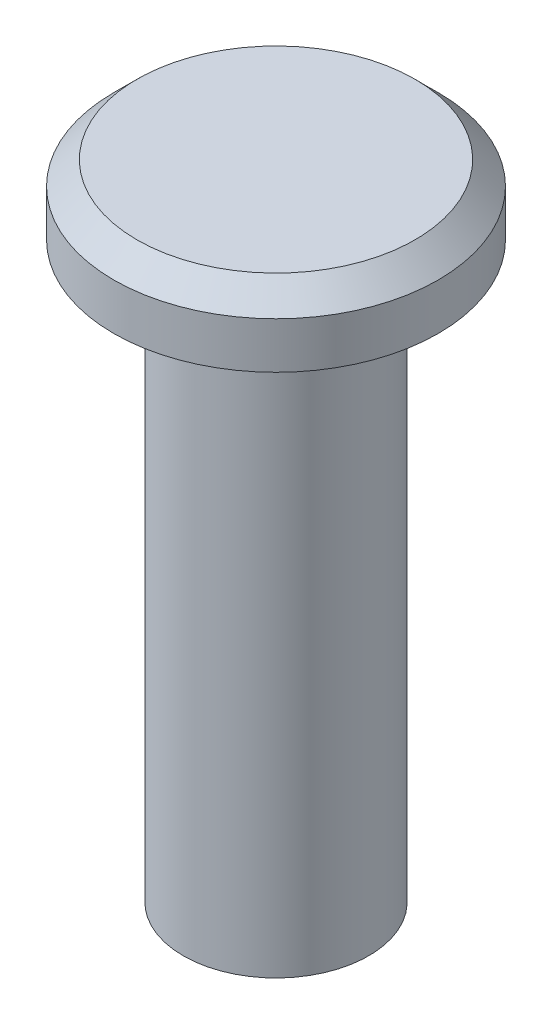
SolidWorks part; units mm, degrees
ref_plane "Front Plane" through (0, 0, 0) normal (0, 0, 1) x (1, 0, 0)
ref_plane "Top Plane" through (0, 0, 0) normal (0, 1, 0) x (1, 0, 0)
ref_plane "Right Plane" through (0, 0, 0) normal (1, 0, 0) x (0, 0, -1)
sketch "Sketch2" plane through (0, 0, 0) normal (0, 1, 0) x (1, 0, 0)
  circle A0 centre (0, 0) radius 7
  dimension "D1" = 14
extrude "Boss-Extrude1" add sketch "Sketch2" along normal blind 3
sketch "Sketch3" plane through (0, 0, 0) normal (0, -1, 0) x (1, 0, 0)
  circle A0 centre (0, 0) radius 4
  dimension "D1" = 8
extrude "Boss-Extrude2" add sketch "Sketch3" along normal blind 24.75
cosmetic thread "Cosmetic Thread1" parameters "D1"=3, "D2"=6.561
chamfer "Chamfer1" distance 1 angle 45 1 edges at (0, 3, 7)
